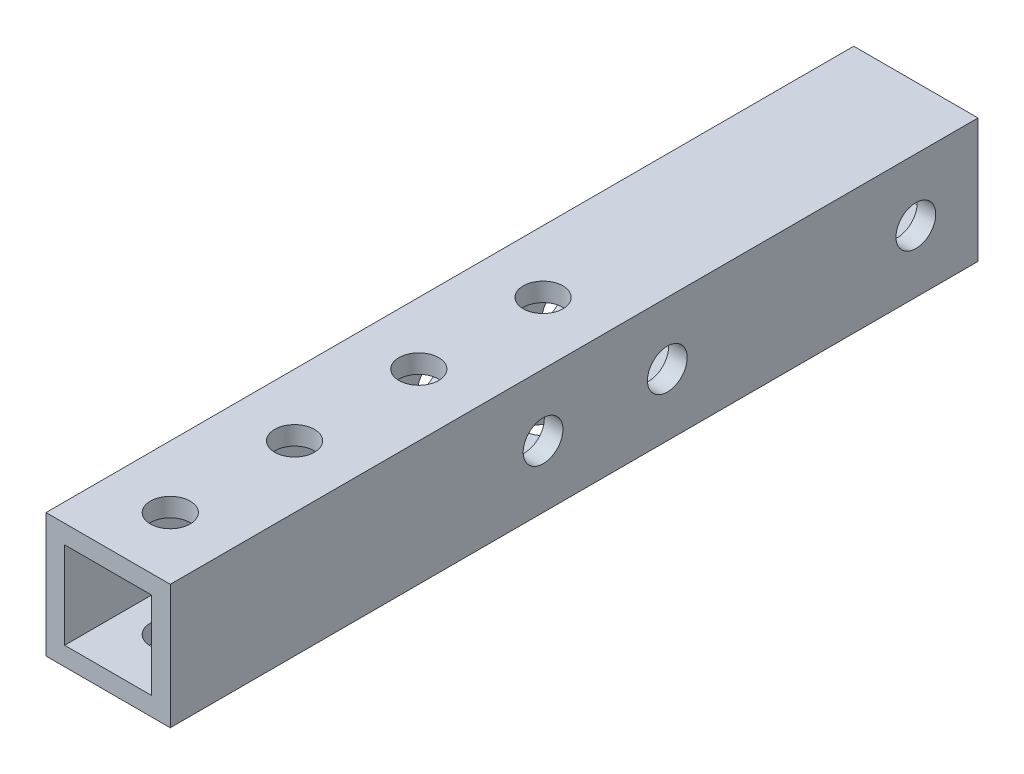
SolidWorks part; units mm, degrees
material "1060 合金"
ref_plane "正面" through (0, 0, 0) normal (0, 0, 1) x (1, 0, 0)
ref_plane "平面" through (0, 0, 0) normal (0, 1, 0) x (1, 0, 0)
ref_plane "右側面" through (0, 0, 0) normal (1, 0, 0) x (0, 0, -1)
sketch "ｽｹｯﾁ1" plane through (0, 0, 0) normal (0, 0, 1) x (1, 0, 0)
  line L1 (-5, -5) -> (5, -5)
  line L2 (-5, -5) -> (-5, 5)
  line L3 (-5, 5) -> (5, 5)
  line L4 (5, -5) -> (5, 5)
  line L5 (-5, -5) -> (5, 5) construction
  line L6 (-5, 5) -> (5, -5) construction
  point P0 (0, 0)
  dimension "D2" = 10
extrude "押し出し-薄板1" add sketch "ｽｹｯﾁ1" along normal blind 65 thin thin type one direction reverse wall 1.5
sketch "ｽｹｯﾁ3" plane through (-5, 0, 0) normal (-1, 0, 0) x (0, 0, 1)
  line L0 (0, 0) -> (65, 0) construction
  line L1 (65, 5) -> (65, -5) construction
  line L2 (0, 5) -> (0, -5) construction
  circle A0 centre (5, 0) radius 1.6
  circle A2 centre (25, 0) radius 1.6
  circle A7 centre (45, 0) radius 1.6 [skipped]
  circle A8 centre (65, 0) radius 1.6 [skipped]
  circle A9 centre (85, 0) radius 1.6 [skipped]
  circle A10 centre (105, 0) radius 1.6 [skipped]
  dimension "D1" = 3.2
  dimension "D2" = 5
  dimension "D4" = 20
  dimension "D3" = 6
extrude "ｶｯﾄ - 押し出し1" cut sketch "ｽｹｯﾁ3" against normal through all
sketch "ｽｹｯﾁ4" plane through (0, -5, 0) normal (0, -1, 0) x (1, 0, 0)
  line L0 (-5, 60) -> (5, 60) construction
  line L1 (-5, 65) -> (-5, 0) construction
  line L2 (5, 65) -> (5, 0) construction
  line L3 (0, 65) -> (0, 0) construction
  line L4 (-5, 65) -> (5, 65) construction
  line L5 (-5, 0) -> (5, 0) construction
  line L6 (0, 145) -> (0, -49855) construction
  circle A0 centre (0, 60) radius 1.6
  circle A1 centre (0, 60) radius 1.6
  circle A2 centre (0, 50) radius 1.6
  circle A3 centre (0, 50) radius 1.6
  circle A4 centre (0, 40) radius 1.6
  circle A5 centre (0, 40) radius 1.6
  circle A6 centre (0, 30) radius 1.6
  circle A7 centre (0, 30) radius 1.6
  dimension "D2" = 3.2
  dimension "D3" = 5
  dimension "D7" = 10
  dimension "D1" = 5
  dimension "D4" = 5
  dimension "D5" = 2
  dimension "D6" = 4
extrude "ｶｯﾄ - 押し出し2" cut sketch "ｽｹｯﾁ4" against normal through all contours A6 | A4 | A2 | A0
sketch "ｽｹｯﾁ5" plane through (5, 0, 0) normal (1, 0, 0) x (0, 0, -1)
  line L0 (-65, 0) -> (0, 0) construction
  line L1 (-65, -5) -> (-65, 5) construction
  circle A0 centre (-35, 0) radius 1.6
  circle A1 centre (-25, 0) radius 1.6 construction
  dimension "D1" = 30
extrude "ｶｯﾄ - 押し出し3" cut sketch "ｽｹｯﾁ5" against normal through all
